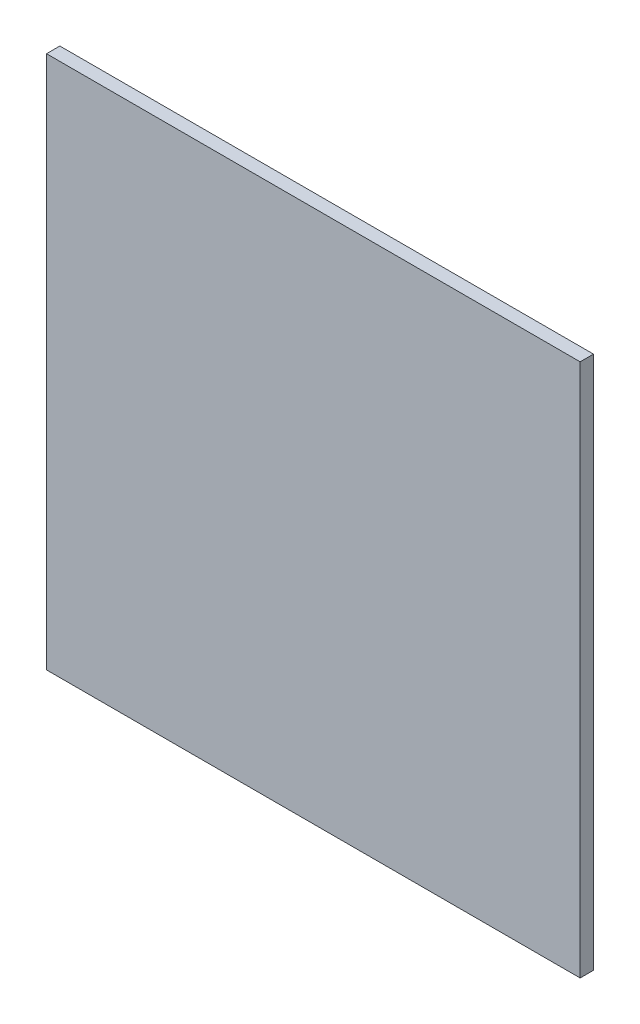
SolidWorks part; units mm, degrees
ref_plane "前视基准面" through (0, 0, 0) normal (0, 0, 1) x (1, 0, 0)
ref_plane "上视基准面" through (0, 0, 0) normal (0, 1, 0) x (1, 0, 0)
ref_plane "右视基准面" through (0, 0, 0) normal (1, 0, 0) x (0, 0, -1)
other "Configuration Table"
sketch "草图1" plane through (0, 0, 0) normal (0, 0, 1) x (1, 0, 0)
  line L1 (0, 0) -> (20, 0)
  line L2 (0, 0) -> (0, 20)
  line L3 (0, 20) -> (20, 20)
  line L4 (20, 0) -> (20, 20)
  dimension "D1" = 20
  dimension "D2" = 20
extrude "凸台-拉伸1" add sketch "草图1" along normal blind 0.5
